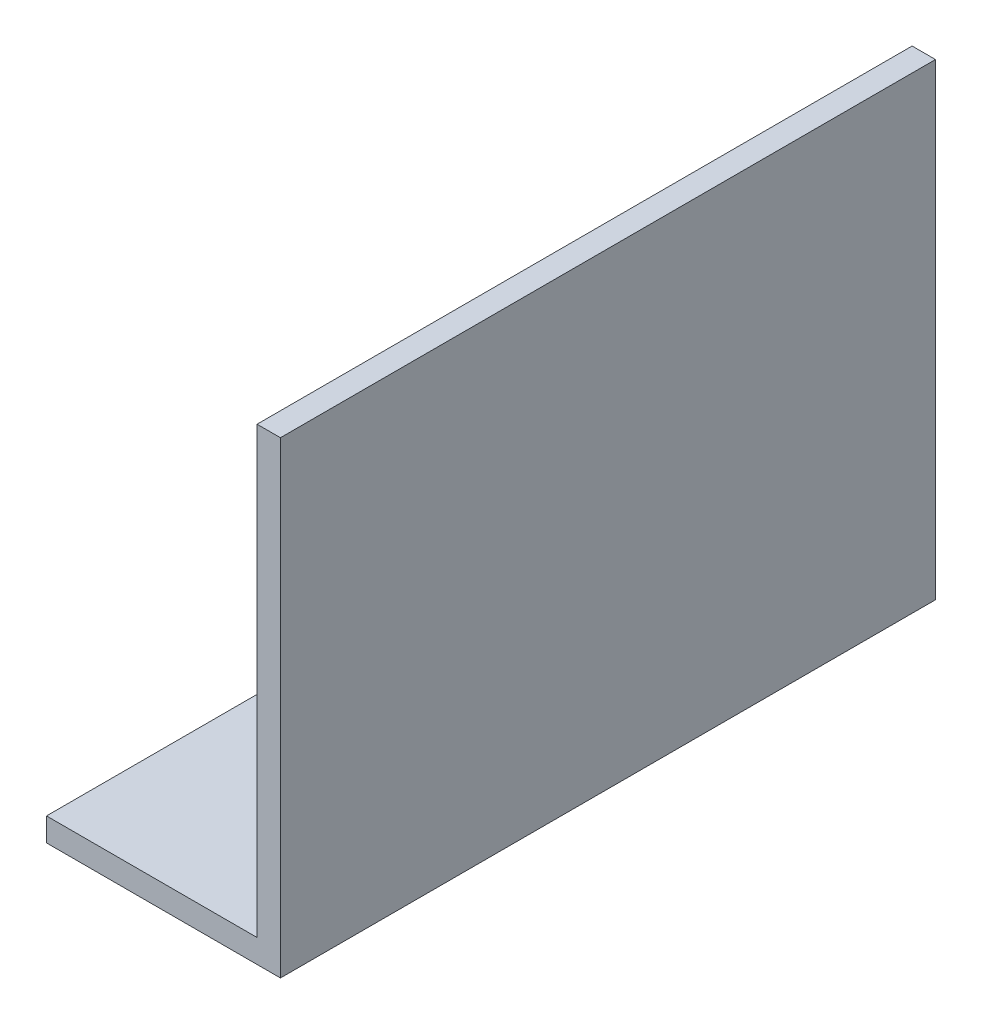
SolidWorks part; units mm, degrees
ref_plane "Front Plane" through (0, 0, 0) normal (0, 0, 1) x (1, 0, 0)
ref_plane "Top Plane" through (0, 0, 0) normal (0, 1, 0) x (1, 0, 0)
ref_plane "Right Plane" through (0, 0, 0) normal (1, 0, 0) x (0, 0, -1)
sketch "Sketch1" plane through (0, 0, 0) normal (0, 0, 1) x (1, 0, 0)
  line L0 (0, 0) -> (0, -100)
  line L6 (0, -100) -> (-50, -100)
  line L7 (-50, -100) -> (-50, -95)
  line L8 (-50, -95) -> (-5, -95)
  line L9 (-5, -95) -> (-5, 0)
  line L10 (-5, 0) -> (0, 0)
  dimension "D3" = 100
  dimension "D5" = 5
  dimension "D6" = 50
  dimension "D1" = 5
extrude "Boss-Extrude1" add sketch "Sketch1" along normal blind 140
equation "\"D1@Sketch1\"=\"D5@Sketch1\""
